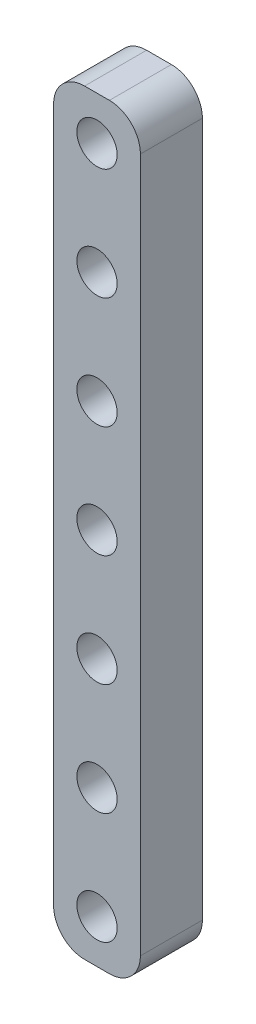
SolidWorks part; units mm, degrees
ref_plane "Front Plane" through (0, 0, 0) normal (0, 0, 1) x (1, 0, 0)
ref_plane "Top Plane" through (0, 0, 0) normal (0, 1, 0) x (1, 0, 0)
ref_plane "Right Plane" through (0, 0, 0) normal (1, 0, 0) x (0, 0, -1)
sketch "Sketch1" plane through (0, 0, 0) normal (0, 0, 1) x (1, 0, 0)
  line L0 (0, 0) -> (0, 100) construction
  line L1 (-2, 0) -> (-2, 100)
  line L2 (2, 0) -> (2, 100)
  line L8 (-6, -4.631) -> (-6, 104.631)
  line L9 (-6, 104.631) -> (6, 104.631)
  line L10 (6, 104.631) -> (6, -4.631)
  line L11 (6, -4.631) -> (-6, -4.631)
  arc A0 (-2, 0) -> (2, 0) centre (0, 0) ccw
  arc A1 (2, 100) -> (-2, 100) centre (0, 100) ccw
  point P3 (0, 50)
  dimension "D5" = 4.631
  dimension "D1" = 4
  dimension "D2" = 4.631
  dimension "D3" = 100
  dimension "D6" = 4
  dimension "D7" = 4
extrude "Boss-Extrude1" add sketch "Sketch1" along normal blind 4
fillet "Fillet1" radius 5 2 edges at (6, -4.631, 2) (-6, -4.631, 2)
sketch "Sketch2" plane through (0, 0, 4) normal (0, 0, 1) x (1, 0, 0)
  line L0 (0, 98.631) -> (0, 1.369) construction
  line L1 (2, 98.631) -> (2, 1.369)
  line L2 (-2, 98.631) -> (-2, 1.369)
  line L3 (6, 104.631) -> (6, 0.369) construction
  line L6 (1, -4.631) -> (-1, -4.631) construction
  line L7 (-6, 104.631) -> (6, 104.631) construction
  arc A0 (2, 98.631) -> (-2, 98.631) centre (0, 98.631) ccw
  arc A1 (-2, 1.369) -> (2, 1.369) centre (0, 1.369) ccw
  point P2 (0, 50)
  dimension "D2" = 6
  dimension "D1" = 4
  dimension "D3" = 6
extrude "Cut-Extrude1" cut sketch "Sketch2" against normal blind 10.5
sketch "Sketch4" plane through (0, 0, 4) normal (0, 0, 1) x (1, 0, 0)
  line L1 (-6, 104.631) -> (6, 104.631)
  line L2 (-6, 104.631) -> (-6, 111.3692)
  line L3 (-6, 111.3692) -> (6, 111.3692)
  line L4 (6, 104.631) -> (6, 111.3692)
extrude "Boss-Extrude2" add sketch "Sketch4" against normal up to surface (4 mm away) up to face at (0, 50, 0)
sketch "Sketch5" plane through (0, 0, 0) normal (0, 0, -1) x (-1, 0, 0)
  line L6 (-7, 117.3692) -> (7, 117.3692)
  line L7 (-7, 117.3692) -> (-7, -4.631)
  line L8 (-7, -4.631) -> (7, -4.631)
  line L9 (7, 117.3692) -> (7, -4.631)
  line L13 (-2, 1.369) -> (-2, 98.631) construction
  dimension "D3" = 5
  dimension "D1" = 0
  dimension "D2" = 14
extrude "Boss-Extrude3" add sketch "Sketch5" along normal blind 6 and the other way up to surface (4 mm away) other way up to face at (0, 50, 4)
sketch "Sketch6" plane through (0, 0, -6) normal (0, 0, -1) x (-1, 0, 0)
  line L0 (7, -4.631) -> (7, 117.3692) construction
  line L1 (7, 117.3692) -> (-7, 117.3692) construction
  circle A0 centre (0, 110.3692) radius 3.25
  dimension "D1" = 6.5
  dimension "D2" = 7
  dimension "D3" = 7
extrude "Cut-Extrude3" cut sketch "Sketch6" against normal up to surface (10 mm away) up to face at (0, 56.3691, 4)
fillet "Fillet2" radius 5 4 edges at (7, -4.631, -1) (7, 117.3692, -1) (-7, 117.3692, -1) (-7, -4.631, -1)
pattern_linear "LPattern1" count 7 spacing 18 along (0, -1, 0) of "Cut-Extrude3"
